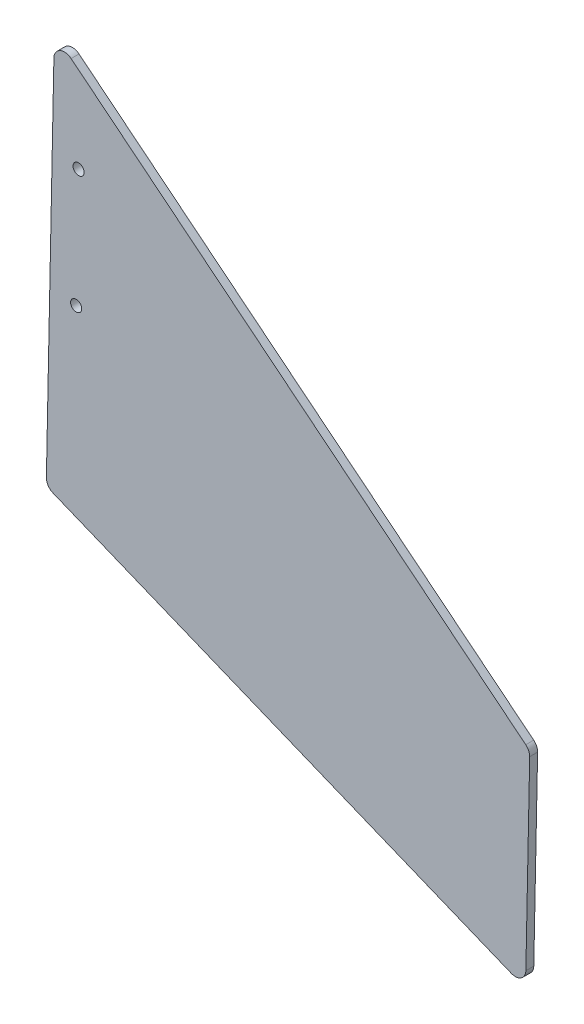
SolidWorks part; units mm, degrees
ref_plane "Спереди" through (0, 0, 0) normal (0, 0, 1) x (1, 0, 0)
ref_plane "Сверху" through (0, 0, 0) normal (0, 1, 0) x (1, 0, 0)
ref_plane "Справа" through (0, 0, 0) normal (1, 0, 0) x (0, 0, -1)
sketch "Эскиз1" plane through (0, 0, 0) normal (0, 0, 1) x (1, 0, 0)
  line L0 (0, 0) -> (-3.0687, -150)
  line L1 (-3.0687, -150) -> (178.4558, -224)
  line L2 (178.4558, -224) -> (180.0657, -145.3026)
  line L3 (180.0657, -145.3026) -> (0, 0)
  dimension "D1" = 150
  dimension "D2" = 224
  dimension "D3" = 183
  dimension "D4" = 183
extrude "Бобышка-Вытянуть1" add sketch "Эскиз1" along normal blind 3 contours L3 L0 L1 L2
fillet "Скругление1" radius 4 4 edges at (-3.0687, -150, 1.5) (0, 0, 1.5) (178.4558, -224, 1.5) (180.0657, -145.3026, 1.5)
sketch "Эскиз2" plane through (0, 0, 3) normal (0, 0, 1) x (1, 0, 0)
  line L0 (-0.1667, -8.1506) -> (-3.0124, -147.2518) construction
  circle A0 centre (9.1838, -40) radius 2.1
  circle A1 centre (8.2593, -85.1905) radius 2.1
  dimension "D1" = 4.2
  dimension "D4" = 4.2
  dimension "D2" = 10
  dimension "D3" = 45.2
  dimension "D5" = 10
  dimension "D6" = 40
extrude "Вырез-Вытянуть1" cut sketch "Эскиз2" against normal blind 3
